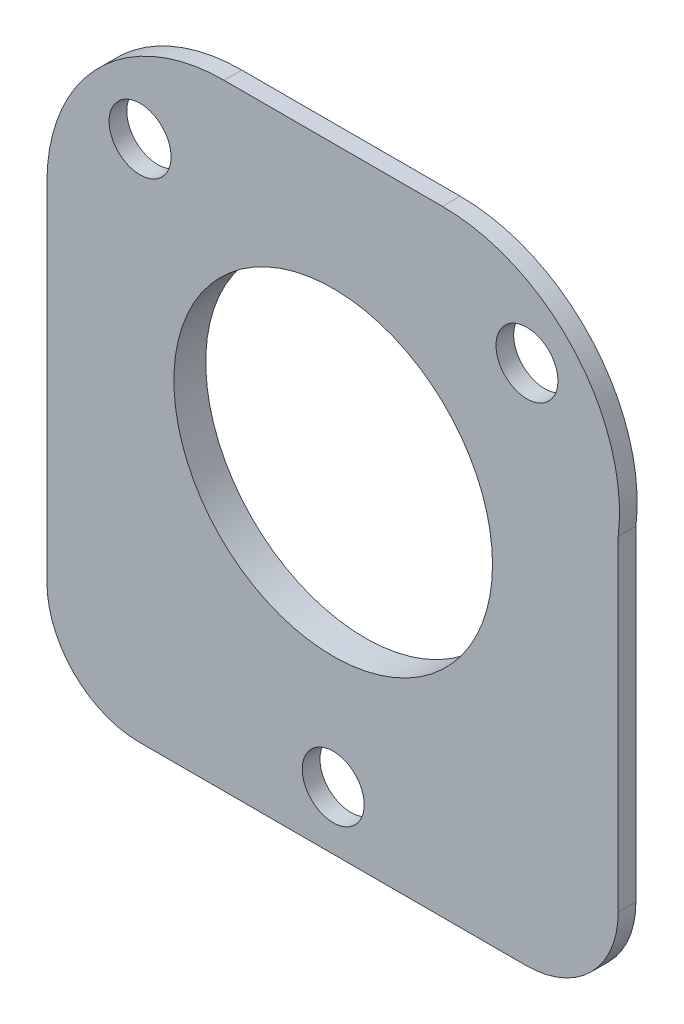
SolidWorks part; units mm, degrees
ref_plane "Piano frontale" through (0, 0, 0) normal (0, 0, 1) x (1, 0, 0)
ref_plane "Piano superiore" through (0, 0, 0) normal (0, 1, 0) x (1, 0, 0)
ref_plane "Piano destro" through (0, 0, 0) normal (1, 0, 0) x (0, 0, -1)
sketch "Schizzo1" plane through (0, 0, 0) normal (0, 0, 1) x (1, 0, 0)
  line L0 (-6.1713, 16.1) -> (6.1713, 16.1) construction
  line L1 (-6.1713, 16.1) -> (6.1713, 16.1)
  line L2 (-16.1713, 6.1) -> (-16.1713, -13.4632)
  line L3 (-10.9575, -18.677) -> (10.8862, -18.677)
  line L4 (16.1, -13.4632) -> (16.1, 4.9079)
  line L5 (-10.9107, 10.852) -> (-13.2424, 13.1711) construction
  line L6 (0, -15.3886) -> (-0.0357, -18.677) construction
  circle A0 centre (0, -15.3886) radius 1.25 construction
  circle A1 centre (0, 0) radius 12.1 construction
  circle A2 centre (-10.9107, 10.852) radius 1.25 construction
  circle A3 centre (10.9445, 10.818) radius 1.25 construction
  arc A4 (16.1, 4.9079) -> (6.1713, 16.1) centre (6.1713, 6.1) ccw construction
  arc A5 (-6.1713, 16.1) -> (-16.1713, 6.1) centre (-6.1713, 6.1) ccw construction
  circle A6 centre (0, -15.3886) radius 1.25
  circle A7 centre (0, 0) radius 12.1
  circle A8 centre (-10.9107, 10.852) radius 1.25
  circle A9 centre (10.9445, 10.818) radius 1.25
  arc A10 (16.1, 4.9079) -> (6.1713, 16.1) centre (6.1713, 6.1) ccw
  arc A11 (-6.1713, 16.1) -> (-16.1713, 6.1) centre (-6.1713, 6.1) ccw
  arc A12 (-16.1713, -13.4632) -> (-10.9575, -18.677) centre (-10.9575, -13.4632) ccw
  arc A13 (10.8862, -18.677) -> (16.1, -13.4632) centre (10.8862, -13.4632) ccw
  circle A14 centre (-10.9107, 10.852) radius 1.75
  circle A15 centre (10.9445, 10.818) radius 1.75
  circle A16 centre (0, -15.3886) radius 1.75
  dimension "D1" = 3.5
extrude "Estrusione-Estrusione1" add sketch "Schizzo1" along normal blind 1 contours L3 A13 L4 A10 L1 A11 L2 A12 A16 A15 A14 A7
sketch "Schizzo2" plane through (0, 0, 1) normal (0, 0, 1) x (1, 0, 0)
  circle A0 centre (0, 0) radius 9 construction
  circle A1 centre (0, 0) radius 9
  circle A2 centre (0, 0) radius 12.1 construction
  circle A3 centre (0, 0) radius 12.1
extrude "Estrusione-Estrusione2" add sketch "Schizzo2" against normal blind 1.8
